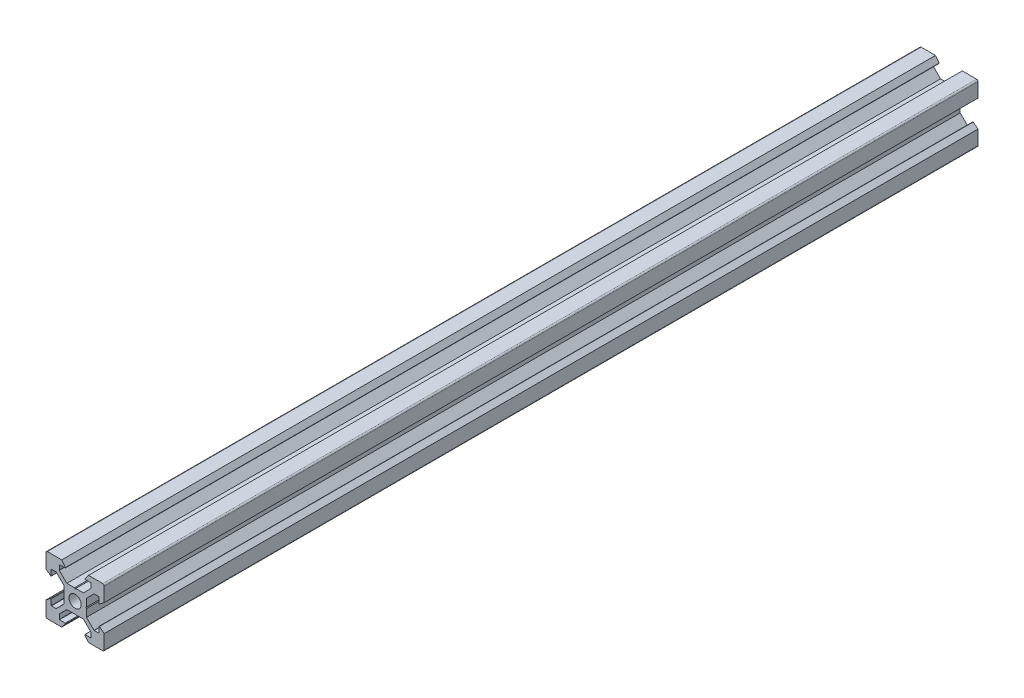
SolidWorks part; units mm, degrees
ref_plane "Front Plane" through (0, 0, 0) normal (0, 0, 1) x (1, 0, 0)
ref_plane "Top Plane" through (0, 0, 0) normal (0, 1, 0) x (1, 0, 0)
ref_plane "Right Plane" through (0, 0, 0) normal (1, 0, 0) x (0, 0, -1)
sketch "Sketch1" plane through (0, 0, 0) normal (0, 0, 1) x (1, 0, 0)
  line L0 (-4.6, 10) -> (-3.3255, 8.3614)
  line L1 (10, 10) -> (-10, 10)
  line L2 (10, 10) -> (10, -10)
  line L3 (10, -10) -> (-10, -10)
  line L4 (-10, 10) -> (-10, -10)
  line L5 (10, 10) -> (-10, -10) construction
  line L6 (10, -10) -> (-10, 10) construction
  line L7 (-3.4045, 8.2) -> (-5.3474, 8.2)
  line L8 (-5.4474, 8.1) -> (-5.4474, 6.5495)
  line L9 (-5.4181, 6.4788) -> (-2.8393, 3.9)
  line L10 (-2.8393, 3.9) -> (-0.2121, 3.9)
  line L11 (0, 0) -> (-13.4195, 0) construction
  line L12 (0, 0) -> (0, 13.908) construction
  line L13 (-0.2121, 3.9) -> (0, 3.6879)
  line L14 (-3.9, 0.2121) -> (-3.6879, 0)
  line L15 (-3.9, 2.8393) -> (-3.9, 0.2121)
  line L16 (-6.4788, 5.4181) -> (-3.9, 2.8393)
  line L17 (-8.1, 5.4474) -> (-6.5495, 5.4474)
  line L18 (-8.2, 3.4045) -> (-8.2, 5.3474)
  line L19 (-10, 4.6) -> (-8.3614, 3.3255)
  line L20 (10, 4.6) -> (8.3614, 3.3255)
  line L21 (8.2, 3.4045) -> (8.2, 5.3474)
  line L22 (8.1, 5.4474) -> (6.5495, 5.4474)
  line L23 (6.4788, 5.4181) -> (3.9, 2.8393)
  line L24 (3.9, 2.8393) -> (3.9, 0.2121)
  line L25 (3.9, 0.2121) -> (3.6879, 0)
  line L26 (0.2121, 3.9) -> (0, 3.6879)
  line L27 (2.8393, 3.9) -> (0.2121, 3.9)
  line L28 (5.4181, 6.4788) -> (2.8393, 3.9)
  line L29 (5.4474, 8.1) -> (5.4474, 6.5495)
  line L30 (3.4045, 8.2) -> (5.3474, 8.2)
  line L31 (4.6, 10) -> (3.3255, 8.3614)
  line L32 (0, 0) -> (0, 13.4195) construction
  line L33 (4.6, -10) -> (3.3255, -8.3614)
  line L34 (3.4045, -8.2) -> (5.3474, -8.2)
  line L35 (5.4474, -8.1) -> (5.4474, -6.5495)
  line L36 (5.4181, -6.4788) -> (2.8393, -3.9)
  line L37 (2.8393, -3.9) -> (0.2121, -3.9)
  line L38 (0.2121, -3.9) -> (0, -3.6879)
  line L39 (3.9, -0.2121) -> (3.6879, 0)
  line L40 (3.9, -2.8393) -> (3.9, -0.2121)
  line L41 (6.4788, -5.4181) -> (3.9, -2.8393)
  line L42 (8.1, -5.4474) -> (6.5495, -5.4474)
  line L43 (8.2, -3.4045) -> (8.2, -5.3474)
  line L44 (10, -4.6) -> (8.3614, -3.3255)
  line L45 (0, 0) -> (13.4195, 0) construction
  line L46 (-10, -4.6) -> (-8.3614, -3.3255)
  line L47 (-8.2, -3.4045) -> (-8.2, -5.3474)
  line L48 (-8.1, -5.4474) -> (-6.5495, -5.4474)
  line L49 (-6.4788, -5.4181) -> (-3.9, -2.8393)
  line L50 (-3.9, -2.8393) -> (-3.9, -0.2121)
  line L51 (-3.9, -0.2121) -> (-3.6879, 0)
  line L52 (-0.2121, -3.9) -> (0, -3.6879)
  line L53 (-2.8393, -3.9) -> (-0.2121, -3.9)
  line L54 (-5.4181, -6.4788) -> (-2.8393, -3.9)
  line L55 (-5.4474, -8.1) -> (-5.4474, -6.5495)
  line L56 (-3.4045, -8.2) -> (-5.3474, -8.2)
  line L57 (-4.6, -10) -> (-3.3255, -8.3614)
  line L58 (0, 0) -> (0, -13.4195) construction
  arc A0 (-5.4474, 6.5495) -> (-5.4181, 6.4788) centre (-5.3474, 6.5495) ccw
  arc A1 (-5.3474, 8.2) -> (-5.4474, 8.1) centre (-5.3474, 8.1) ccw
  arc A2 (-3.3255, 8.3614) -> (-3.4045, 8.2) centre (-3.4045, 8.3) cw
  arc A3 (-6.5495, 5.4474) -> (-6.4788, 5.4181) centre (-6.5495, 5.3474) cw
  arc A4 (-8.2, 5.3474) -> (-8.1, 5.4474) centre (-8.1, 5.3474) cw
  arc A5 (-8.3614, 3.3255) -> (-8.2, 3.4045) centre (-8.3, 3.4045) ccw
  arc A6 (6.5495, 5.4474) -> (6.4788, 5.4181) centre (6.5495, 5.3474) ccw
  arc A7 (8.2, 5.3474) -> (8.1, 5.4474) centre (8.1, 5.3474) ccw
  arc A8 (8.3614, 3.3255) -> (8.2, 3.4045) centre (8.3, 3.4045) cw
  arc A9 (5.4474, 6.5495) -> (5.4181, 6.4788) centre (5.3474, 6.5495) cw
  arc A10 (5.3474, 8.2) -> (5.4474, 8.1) centre (5.3474, 8.1) cw
  arc A11 (3.3255, 8.3614) -> (3.4045, 8.2) centre (3.4045, 8.3) ccw
  arc A12 (5.4474, -6.5495) -> (5.4181, -6.4788) centre (5.3474, -6.5495) ccw
  arc A13 (5.3474, -8.2) -> (5.4474, -8.1) centre (5.3474, -8.1) ccw
  arc A14 (3.3255, -8.3614) -> (3.4045, -8.2) centre (3.4045, -8.3) cw
  arc A15 (6.5495, -5.4474) -> (6.4788, -5.4181) centre (6.5495, -5.3474) cw
  arc A16 (8.2, -5.3474) -> (8.1, -5.4474) centre (8.1, -5.3474) cw
  arc A17 (8.3614, -3.3255) -> (8.2, -3.4045) centre (8.3, -3.4045) ccw
  arc A18 (-6.5495, -5.4474) -> (-6.4788, -5.4181) centre (-6.5495, -5.3474) ccw
  arc A19 (-8.2, -5.3474) -> (-8.1, -5.4474) centre (-8.1, -5.3474) ccw
  arc A20 (-8.3614, -3.3255) -> (-8.2, -3.4045) centre (-8.3, -3.4045) cw
  arc A21 (-5.4474, -6.5495) -> (-5.4181, -6.4788) centre (-5.3474, -6.5495) cw
  arc A22 (-5.3474, -8.2) -> (-5.4474, -8.1) centre (-5.3474, -8.1) cw
  arc A23 (-3.3255, -8.3614) -> (-3.4045, -8.2) centre (-3.4045, -8.3) ccw
  circle A24 centre (0, 0) radius 2.1
  point P0 (0, 0)
  point P23 (-3.2, 8.2)
  point P39 (0, 0)
  point P67 (0, 0)
  point P95 (0, 0)
  point P123 (0, 0)
  dimension "D10" = 0.1
  dimension "4.2" = 4.2
  dimension "D1" = 20
  dimension "D2" = 20
  dimension "D3" = 3.2
  dimension "D4" = 4.6
  dimension "D5" = 4.3
  dimension "D6" = 1.8
  dimension "D7" = 0.75
  dimension "D8" = 0.3
  dimension "D9" = 45
  dimension "D11" = 4
extrude "Boss-Extrude1" add sketch "Sketch1" against normal blind 300 contours L57 A23 L56 A22 L55 A21 L54 L53 L52 L38 L37 L36 A12 L35 A13 L34 A14 L33 L3 L2 L44 A17 L43 A16 L42 A15 L41 L40 L39 L25 L24 L23 A6 L22 A7 L21 A8 L20 L1 L31 A11 L30 A10 L29 A9 L28 L27 L26 L13 L10
fillet "Fillet1" radius 0.5 4 edges at (-10, -10, -150) (10, -10, -150) (-10, 10, -150) (10, 10, -150)
